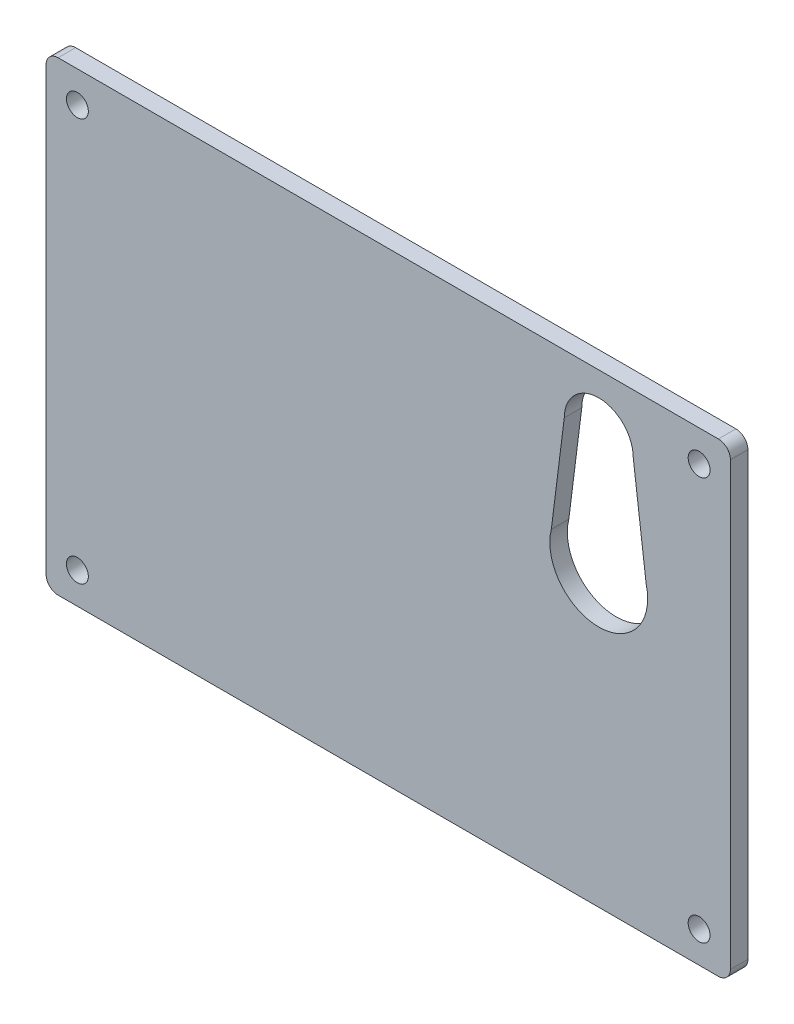
SolidWorks part; units mm, degrees
ref_plane "Front Plane" through (0, 0, 0) normal (0, 0, 1) x (1, 0, 0)
ref_plane "Top Plane" through (0, 0, 0) normal (0, 1, 0) x (1, 0, 0)
ref_plane "Right Plane" through (0, 0, 0) normal (1, 0, 0) x (0, 0, -1)
sketch "Sketch1" plane through (0, 0, 0) normal (0, 0, 1) x (1, 0, 0)
  line L0 (20.8751, 13.4244) -> (20.8751, 0.7244) construction
  line L1 (23.4151, -1.8156) -> (43.7351, -1.8156) construction
  line L2 (46.2751, 0.7244) -> (46.2751, 13.4244) construction
  line L3 (43.7351, 15.9644) -> (23.4151, 15.9644) construction
  line L12 (-29.6649, 25.9244) -> (-29.6649, -24.4756) construction
  line L13 (-28.1649, -25.9756) -> (47.2351, -25.9756) construction
  line L14 (48.7351, -24.4756) -> (48.7351, 25.9244) construction
  line L15 (47.2351, 27.4244) -> (-28.1649, 27.4244) construction
  line L16 (20.8751, 13.4244) -> (20.8751, 0.7244) construction
  line L17 (23.4151, -1.8156) -> (43.7351, -1.8156) construction
  line L18 (46.2751, 0.7244) -> (46.2751, 13.4244) construction
  line L19 (43.7351, 15.9644) -> (23.4151, 15.9644) construction
  line L20 (-29.6649, 25.9244) -> (-29.6649, -24.4756) construction
  line L21 (-28.1649, -25.9756) -> (47.2351, -25.9756) construction
  line L22 (48.7351, -24.4756) -> (48.7351, 25.9244) construction
  line L23 (47.2351, 27.4244) -> (-28.1649, 27.4244) construction
  line L24 (47.2351, 27.2994) -> (-28.1649, 27.2994)
  line L25 (-29.5399, 25.9244) -> (-29.5399, -24.4756)
  line L26 (-28.1649, -25.8506) -> (47.2351, -25.8506)
  line L27 (48.6101, -24.4756) -> (48.6101, 25.9244)
  line L28 (37.5121, 20.6027) -> (39.1631, 7.4554)
  line L30 (27.9871, 7.4554) -> (29.6381, 20.6027)
  arc A0 (20.8751, 0.7244) -> (23.4151, -1.8156) centre (23.4151, 0.7244) ccw construction
  circle A1 centre (23.4151, 13.4244) radius 1.25
  circle A2 centre (23.4151, 13.4244) radius 1.25 construction
  circle A3 centre (29.6381, 13.5514) radius 0.2413
  circle A4 centre (29.6381, 13.5514) radius 0.2413 construction
  circle A5 centre (32.0511, 5.0424) radius 0.25
  circle A6 centre (32.0511, 5.0424) radius 0.25 construction
  circle A7 centre (34.9721, 9.3604) radius 0.2413
  circle A8 centre (34.9721, 9.3604) radius 0.2413 construction
  circle A9 centre (31.0351, 0.7244) radius 0.5
  circle A10 centre (31.0351, 0.7244) radius 0.5 construction
  circle A11 centre (42.1231, 10.4644) radius 0.25
  circle A12 centre (42.1231, 10.4644) radius 0.25 construction
  circle A13 centre (42.9731, 5.4234) radius 0.25
  circle A14 centre (42.9731, 5.4234) radius 0.25 construction
  circle A15 centre (24.4311, 7.9634) radius 0.25
  circle A16 centre (24.4311, 7.9634) radius 0.25 construction
  circle A17 centre (23.4151, 0.7244) radius 1.25
  circle A18 centre (23.4151, 0.7244) radius 1.25 construction
  circle A19 centre (24.9391, 4.6614) radius 0.25
  circle A20 centre (24.9391, 4.6614) radius 0.25 construction
  circle A21 centre (38.6551, 0.7244) radius 0.5
  circle A22 centre (38.6551, 0.7244) radius 0.5 construction
  circle A23 centre (38.2551, 7.4554) radius 0.25
  circle A24 centre (38.2551, 7.4554) radius 0.25 construction
  circle A25 centre (28.4951, 0.7244) radius 0.5
  circle A26 centre (28.4951, 0.7244) radius 0.5 construction
  circle A27 centre (35.9881, 4.4074) radius 0.25
  circle A28 centre (35.9881, 4.4074) radius 0.25 construction
  circle A29 centre (24.4311, 9.6144) radius 0.25
  circle A30 centre (24.4311, 9.6144) radius 0.25 construction
  circle A31 centre (40.5601, 9.6144) radius 0.25
  circle A32 centre (40.5601, 9.6144) radius 0.25 construction
  circle A33 centre (43.7351, 13.4244) radius 1.25
  circle A34 centre (43.7351, 13.4244) radius 1.25 construction
  circle A35 centre (25.4471, 11.9004) radius 0.25
  circle A36 centre (25.4471, 11.9004) radius 0.25 construction
  circle A37 centre (33.5751, 0.7244) radius 0.5
  circle A38 centre (33.5751, 0.7244) radius 0.5 construction
  circle A39 centre (27.9871, 11.9004) radius 0.2413
  circle A40 centre (27.9871, 11.9004) radius 0.2413 construction
  circle A41 centre (32.9401, 11.9004) radius 0.25
  circle A42 centre (32.9401, 11.9004) radius 0.25 construction
  circle A43 centre (43.7351, 0.7244) radius 1.25
  circle A44 centre (43.7351, 0.7244) radius 1.25 construction
  circle A45 centre (24.3267, 5.827) radius 0.25
  circle A46 centre (24.3267, 5.827) radius 0.25 construction
  circle A47 centre (36.1151, 0.7244) radius 0.5
  circle A48 centre (36.1151, 0.7244) radius 0.5 construction
  circle A49 centre (42.7191, 7.4554) radius 0.25
  circle A50 centre (42.7191, 7.4554) radius 0.25 construction
  circle A51 centre (-25.9649, -22.2756) radius 1.25
  circle A52 centre (-25.9649, -22.2756) radius 1.25
  circle A53 centre (-25.9649, 23.7244) radius 1.25
  circle A54 centre (-25.9649, 23.7244) radius 1.25
  circle A55 centre (45.0351, 23.7244) radius 1.25
  circle A56 centre (45.0351, 23.7244) radius 1.25
  circle A57 centre (45.0351, -22.2756) radius 1.25
  circle A58 centre (45.0351, -22.2756) radius 1.25
  arc A59 (43.7351, -1.8156) -> (46.2751, 0.7244) centre (43.7351, 0.7244) ccw construction
  arc A60 (46.2751, 13.4244) -> (43.7351, 15.9644) centre (43.7351, 13.4244) ccw construction
  arc A61 (23.4151, 15.9644) -> (20.8751, 13.4244) centre (23.4151, 13.4244) ccw construction
  arc A70 (-29.6649, -24.4756) -> (-28.1649, -25.9756) centre (-28.1649, -24.4756) ccw construction
  arc A71 (47.2351, -25.9756) -> (48.7351, -24.4756) centre (47.2351, -24.4756) ccw construction
  arc A72 (48.7351, 25.9244) -> (47.2351, 27.4244) centre (47.2351, 25.9244) ccw construction
  arc A73 (-28.1649, 27.4244) -> (-29.6649, 25.9244) centre (-28.1649, 25.9244) ccw construction
  arc A74 (20.8751, 0.7244) -> (23.4151, -1.8156) centre (23.4151, 0.7244) ccw construction
  arc A75 (43.7351, -1.8156) -> (46.2751, 0.7244) centre (43.7351, 0.7244) ccw construction
  arc A76 (46.2751, 13.4244) -> (43.7351, 15.9644) centre (43.7351, 13.4244) ccw construction
  arc A77 (23.4151, 15.9644) -> (20.8751, 13.4244) centre (23.4151, 13.4244) ccw construction
  arc A78 (-29.6649, -24.4756) -> (-28.1649, -25.9756) centre (-28.1649, -24.4756) ccw construction
  arc A79 (47.2351, -25.9756) -> (48.7351, -24.4756) centre (47.2351, -24.4756) ccw construction
  arc A80 (48.7351, 25.9244) -> (47.2351, 27.4244) centre (47.2351, 25.9244) ccw construction
  arc A81 (-28.1649, 27.4244) -> (-29.6649, 25.9244) centre (-28.1649, 25.9244) ccw construction
  arc A82 (-28.1649, 27.2994) -> (-29.5399, 25.9244) centre (-28.1649, 25.9244) ccw
  arc A83 (-29.5399, -24.4756) -> (-28.1649, -25.8506) centre (-28.1649, -24.4756) ccw
  arc A84 (47.2351, -25.8506) -> (48.6101, -24.4756) centre (47.2351, -24.4756) ccw
  arc A85 (48.6101, 25.9244) -> (47.2351, 27.2994) centre (47.2351, 25.9244) ccw
  arc A86 (28.1606, 8.837) -> (38.9896, 8.837) centre (33.5751, 7.4554) ccw
  arc A87 (37.5121, 20.6027) -> (29.6381, 20.6027) centre (33.5751, 20.6027) ccw
  point P89 (0, 0)
  point P91 (33.5751, 20.6027)
  dimension "D1" = 0
  dimension "D2" = 0
  dimension "D3" = 0
  dimension "D4" = 0
  dimension "D5" = 0
  dimension "D6" = 0
  dimension "D7" = 0
  dimension "D8" = 0
  dimension "D9" = 0
  dimension "D10" = 0
  dimension "D11" = 0
  dimension "D12" = 0
  dimension "D13" = 0
  dimension "D14" = 0
  dimension "D15" = 0
  dimension "D16" = 0
  dimension "D17" = 0
  dimension "D18" = 0
  dimension "D19" = 0
  dimension "D20" = 0
  dimension "D21" = 0
  dimension "D22" = 0
  dimension "D23" = 0
  dimension "D24" = 0
  dimension "D25" = 0
  dimension "D26" = 0
  dimension "D27" = 0
  dimension "D28" = 0
  dimension "D29" = 0
  dimension "D31" = 0.125
extrude "Boss-Extrude1" add sketch "Sketch1" along normal blind 2
